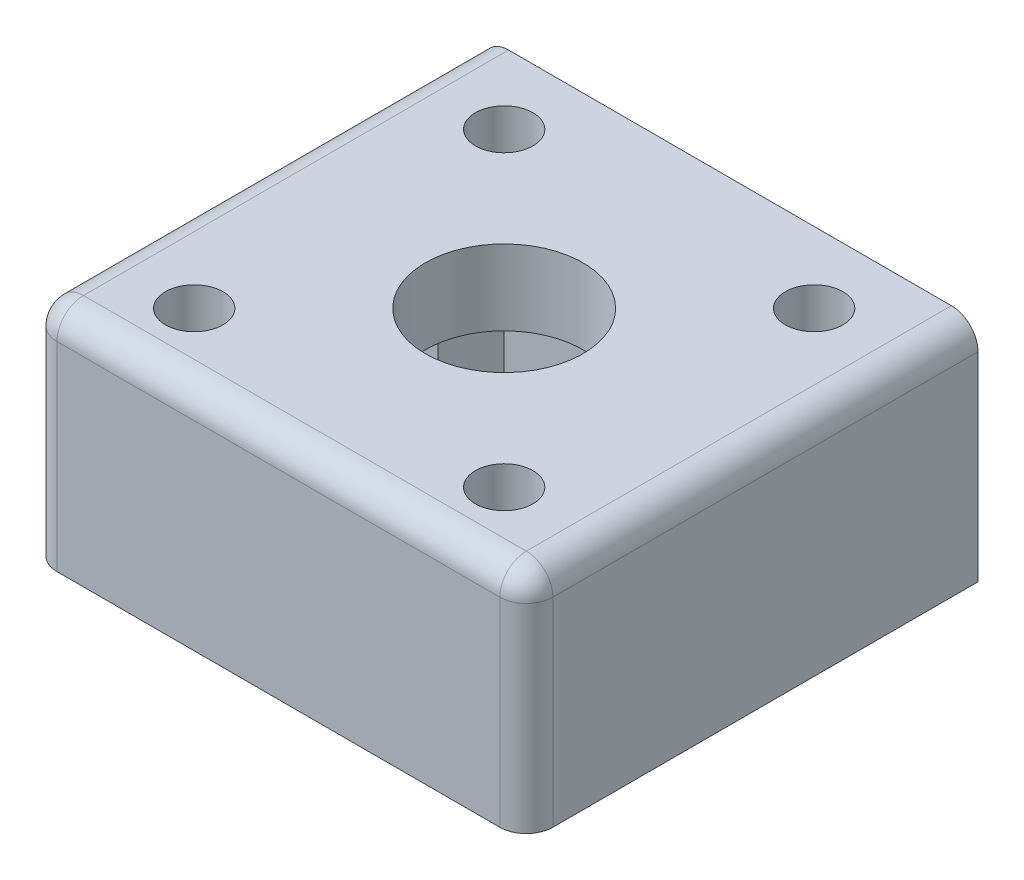
SolidWorks part; units mm, degrees
ref_plane "Front Plane" through (0, 0, 0) normal (0, 0, 1) x (1, 0, 0)
ref_plane "Top Plane" through (0, 0, 0) normal (0, 1, 0) x (1, 0, 0)
ref_plane "Right Plane" through (0, 0, 0) normal (1, 0, 0) x (0, 0, -1)
sketch "Sketch1" plane through (0, 0, 0) normal (0, 1, 0) x (1, 0, 0)
  line L0 (0, 0) -> (0, -15) construction
  line L1 (-28, -25.5) -> (28, -25.5)
  line L2 (-28, -25.5) -> (-28, 25.5)
  line L3 (-28, 25.5) -> (28, 25.5)
  line L4 (28, -25.5) -> (28, 25.5)
  line L5 (-28, -25.5) -> (28, 25.5) construction
  line L6 (-28, 25.5) -> (28, -25.5) construction
  line L7 (-15, -15) -> (15, -15)
  line L8 (-15, -15) -> (-15, 15)
  line L9 (-15, 15) -> (15, 15)
  line L10 (15, -15) -> (15, 15)
  line L11 (-15, -15) -> (15, 15) construction
  line L12 (-15, 15) -> (15, -15) construction
  line L13 (20, -7.5) -> (15, -7.5)
  line L14 (20, -7.5) -> (20, 7.5)
  line L15 (20, 7.5) -> (15, 7.5)
  line L16 (15, -7.5) -> (15, 7.5)
  line L17 (20, -7.5) -> (15, 7.5) construction
  line L18 (20, 7.5) -> (15, -7.5) construction
  line L19 (-20, -7.5) -> (-15, -7.5)
  line L20 (-20, -7.5) -> (-20, 7.5)
  line L21 (-20, 7.5) -> (-15, 7.5)
  point P0 (0, 0)
  point P5 (0, 0)
  point P11 (17.5, 0)
  dimension "D1" = 51
  dimension "D2" = 56
  dimension "D3" = 30
  dimension "D4" = 5
  dimension "D5" = 15
extrude "Boss-Extrude1" add sketch "Sketch1" along normal blind 17 contours L1 L4 L3 L2 L20 L21 L8 L9 L10 L15 L14 L13 L7 L19
sketch "Sketch2" plane through (0, 17, 0) normal (0, 1, 0) x (1, 0, 0)
  line L1 (-28, 25.5) -> (28, 25.5)
  line L2 (-28, 25.5) -> (-28, -25.5)
  line L3 (-28, -25.5) -> (28, -25.5)
  line L4 (28, 25.5) -> (28, -25.5)
  circle A0 centre (0, 0) radius 8.9
  point P7 (0, 0)
  point P8 (0, 0)
  point P11 (0, 0)
  point P12 (-26.7207, 23.9206)
  point P13 (0, 0)
  point P15 (26.4833, -24.1865)
  point P17 (0, 0)
  dimension "D1" = 17.8
extrude "Boss-Extrude2" add sketch "Sketch2" along normal blind 8.5
hole_wizard "CBORE for M3 SHCS1" positions "Sketch3" profile "Sketch4" counterbore size "M3" standard "ANSI Metric" end condition through all
sketch "Sketch3" plane through (0, 25.5, 0) normal (0, 1, 0) x (1, 0, 0)
  line L0 (-28, 25.5) -> (-28, -25.5) construction
  line L1 (28, 25.5) -> (-28, 25.5) construction
  point P0 (-17.5, 17.5)
  point P2 (17.5, 17.5)
  point P4 (17.5, -17.5)
  point P6 (-17.5, -17.5)
  dimension "D1" = 35
  dimension "D2" = 35
  dimension "D3" = 10.5
  dimension "D4" = 8
sketch "Sketch4" plane through (-17.5, 25.5, -17.5) normal (1, 0, 0) x (0, 0, 1)
  line L0 (0, 0) -> (0, 25.5)
  line L1 (0, 25.5) -> (1.8, 25.5)
  line L3 (1.8, 25.5) -> (1.8, 23)
  line L4 (1.8, 23) -> (3.25, 23)
  line L5 (3.25, 23) -> (3.25, 0)
  line L7 (3.25, 0) -> (0, 0)
  line L11 (0, -6.35) -> (0, 107.95) construction
  dimension "Thru Hole Dia." = 3.6
  dimension "Thru Hole Depth" = 25.5
  dimension "C'Bore Dia." = 6.5
  dimension "C'Bore Depth" = 23
fillet "Fillet3" radius 3 2 edges at (28, 25.5, 0) (-28, 25.5, 0)
hole_wizard "M2.5x0.45 Tapped Hole1" positions "Sketch7" profile "Sketch8" tap size "M2.5x0.45" standard "ANSI Metric"
sketch "Sketch7" plane through (0, 0, -25.5) normal (0, 0, -1) x (-1, 0, 0)
  line L0 (-25, 25.5) -> (25, 25.5) construction
  line L1 (28, 22.5) -> (28, 0) construction
  line L2 (-28, 22.5) -> (-28, 0) construction
  line L4 (28, 0) -> (-28, 0) construction
  point P0 (-23, 20.5)
  point P2 (23, 20.5)
  point P11 (-23, 5)
  point P13 (23, 5)
  dimension "D1" = 5
  dimension "D2" = 5
  dimension "D3" = 5
  dimension "D4" = 5
cosmetic thread "Hole Thread1" parameters "D1"=51, "D2"=2.5
cosmetic thread "Hole Thread2" parameters "D1"=51, "D2"=2.5
sketch "Sketch8" plane through (23, 20.5, -25.5) normal (1, 0, 0) x (0, 1, 0)
  line L0 (0, 0) -> (0, 10.6159)
  line L1 (0, 10.6159) -> (1.025, 10)
  line L2 (1.025, 10) -> (1.025, 0)
  line L5 (1.025, 0) -> (0, 0)
  line L10 (0, 10.6159) -> (-1.025, 10) construction
  line L11 (0, -6.35) -> (0, 107.95) construction
  dimension "Tap Drill Dia." = 2.05
  dimension "Tap Drill Depth" = 10
  dimension "Drill Angle" = 118
cosmetic thread "Hole Thread5" parameters "D1"=51, "D2"=2.5
cosmetic thread "Hole Thread6" parameters "D1"=51, "D2"=2.5
fillet "Fillet4" radius 3 5 edges at (-28, 11.25, 25.5) (-27.1213, 24.6213, 25.5) (28, 11.25, 25.5) (27.1213, 24.6213, 25.5) (0, 25.5, 25.5)
